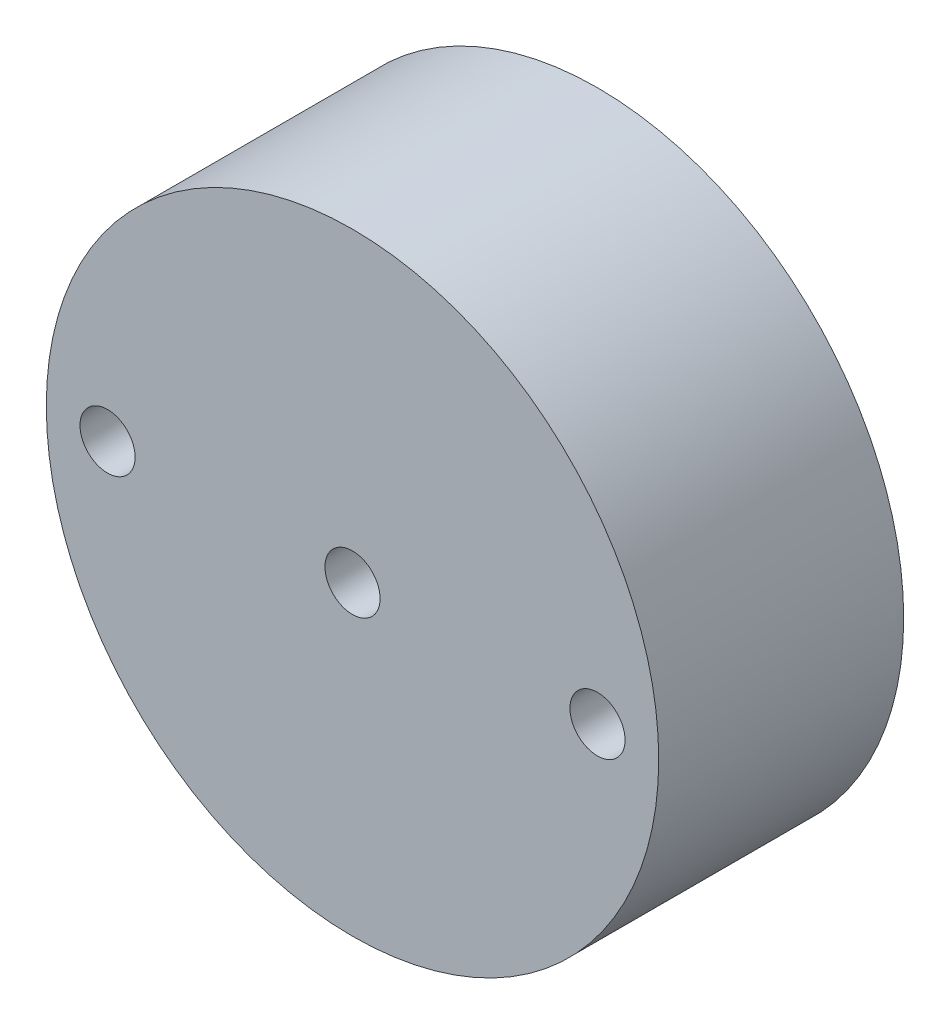
SolidWorks part; units mm, degrees
ref_plane "Front Plane" through (0, 0, 0) normal (0, 0, 1) x (1, 0, 0)
ref_plane "Top Plane" through (0, 0, 0) normal (0, 1, 0) x (1, 0, 0)
ref_plane "Right Plane" through (0, 0, 0) normal (1, 0, 0) x (0, 0, -1)
sketch "Sketch1" plane through (0, 0, 0) normal (0, 0, 1) x (1, 0, 0)
  circle A0 centre (215, -6) radius 2.25 construction
  circle A1 centre (235, -6) radius 25 construction
  circle A2 centre (255, -6) radius 2.25 construction
  circle A3 centre (215, -6) radius 2.25
  circle A4 centre (235, -6) radius 25
  circle A5 centre (255, -6) radius 2.25
  circle A6 centre (235, -6) radius 2.25
extrude "Boss-Extrude1" add sketch "Sketch1" along normal up to surface (20 mm away)
